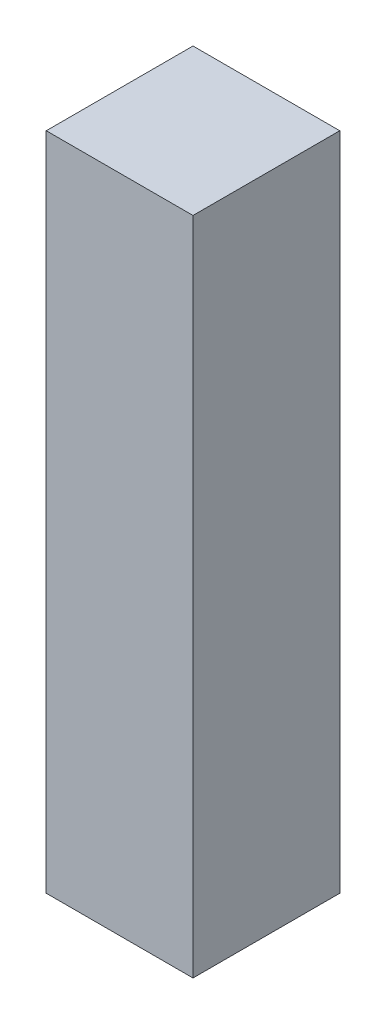
SolidWorks part; units mm, degrees
ref_plane "Front Plane" through (0, 0, 0) normal (0, 0, 1) x (1, 0, 0)
ref_plane "Top Plane" through (0, 0, 0) normal (0, 1, 0) x (1, 0, 0)
ref_plane "Right Plane" through (0, 0, 0) normal (1, 0, 0) x (0, 0, -1)
sketch "Sketch1" plane through (0, 0, 0) normal (0, 1, 0) x (1, 0, 0)
  line L1 (-10, 10) -> (10, 10)
  line L2 (-10, 10) -> (-10, -10)
  line L3 (-10, -10) -> (10, -10)
  line L4 (10, 10) -> (10, -10)
  line L5 (-10, 10) -> (10, -10) construction
  line L6 (-10, -10) -> (10, 10) construction
  point P0 (0, 0)
  dimension "D1" = 20
  dimension "D2" = 20
extrude "Boss-Extrude1" add sketch "Sketch1" along normal blind 90
